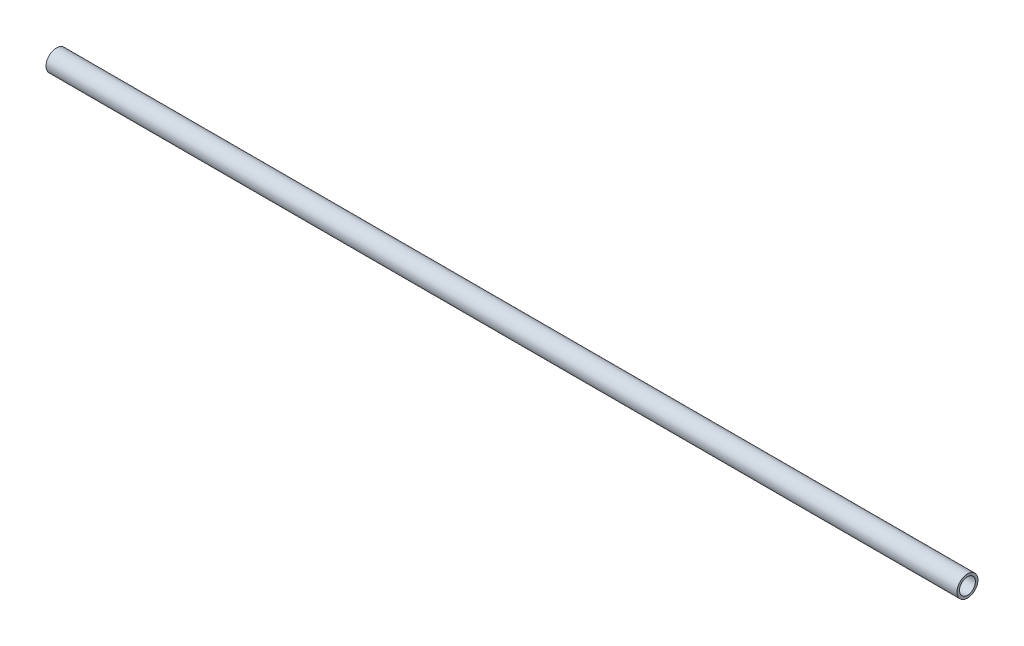
SolidWorks part; units mm, degrees
material "AISI 4130 Steel, annealed at 865C"
ref_plane "Front Plane" through (0, 0, 0) normal (0, 0, 1) x (1, 0, 0)
ref_plane "Top Plane" through (0, 0, 0) normal (0, 1, 0) x (1, 0, 0)
ref_plane "Right Plane" through (0, 0, 0) normal (1, 0, 0) x (0, 0, -1)
sketch "Sketch1" plane through (0, 0, 0) normal (1, 0, 0) x (0, 0, -1)
  circle A0 centre (0, 0) radius 12.7
  circle A1 centre (0, 0) radius 9.652
  dimension "D1" = 25.4
  dimension "D2" = 19.304
extrude "Boss-Extrude1" add sketch "Sketch1" along normal blind 1100
